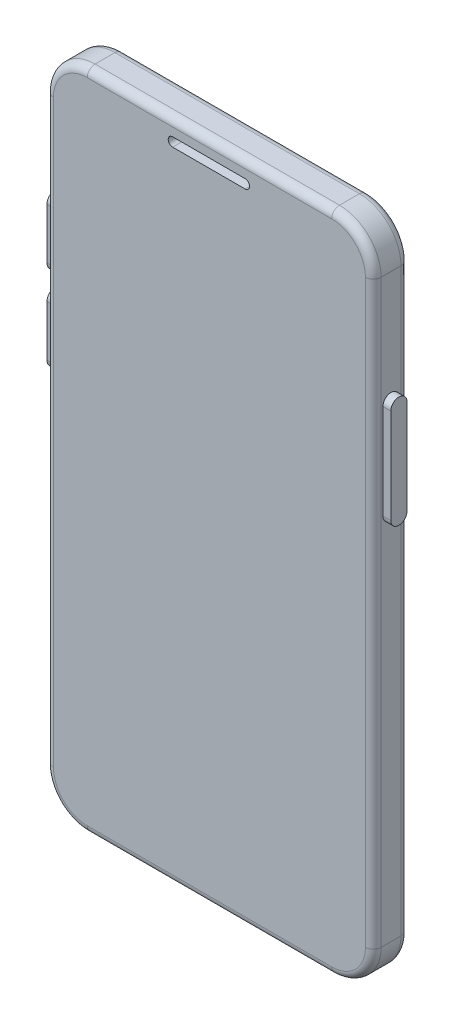
SolidWorks part; units mm, degrees
ref_plane "Front Plane" through (0, 0, 0) normal (0, 0, 1) x (1, 0, 0)
ref_plane "Top Plane" through (0, 0, 0) normal (0, 1, 0) x (1, 0, 0)
ref_plane "Right Plane" through (0, 0, 0) normal (1, 0, 0) x (0, 0, -1)
sketch "Sketch1" plane through (0, 0, 0) normal (0, 0, 1) x (1, 0, 0)
  line L1 (0, 0) -> (70.9, 0)
  line L2 (0, 0) -> (0, -143.6)
  line L3 (0, -143.6) -> (70.9, -143.6)
  line L4 (70.9, 0) -> (70.9, -143.6)
  dimension "D1" = 70.9
  dimension "D2" = 143.6
extrude "Boss-Extrude1" add sketch "Sketch1" along normal blind 7.7
fillet "Fillet1" radius 9 4 edges at (0, -143.6, 3.85) (70.9, -143.6, 3.85) (0, 0, 3.85) (70.9, 0, 3.85)
sketch "Sketch2" plane through (70.9, -8.3279, 0) normal (1, 0, 0) x (0, 0, -1)
  line L0 (-3.85, -9) -> (-3.85, -134.6) construction
  line L5 (-5.6051, -45.632) -> (-5.6051, -25.0925)
  line L7 (-2.0949, -45.632) -> (-2.0949, -25.0925)
  line L8 (-5.6051, -45.632) -> (-2.0949, -25.0925) construction
  line L9 (-5.6051, -25.0925) -> (-2.0949, -45.632) construction
  arc A0 (-2.0949, -25.0925) -> (-5.6051, -25.0925) centre (-3.85, -25.0925) ccw
  arc A1 (-2.0949, -45.632) -> (-5.6051, -45.632) centre (-3.85, -45.632) cw
  point P6 (-3.85, -35.3623)
extrude "Boss-Extrude2" add sketch "Sketch2" along normal blind 1.7 contours L5 A0 L7 A1
sketch "Sketch3" plane through (0, 0, 0) normal (-1, 0, 0) x (0, 0, 1)
  line L0 (3.85, -9) -> (3.85, -120.3552) construction
  line L1 (7.7, -9) -> (0, -9) construction
  line L2 (0, -46.37) -> (7.7, -46.37)
  line L4 (1.9886, -42.7498) -> (1.9886, -31.7534)
  line L6 (5.7114, -42.7498) -> (5.7114, -31.7534)
  line L7 (1.9886, -42.7498) -> (5.7114, -31.7534) construction
  line L8 (1.9886, -31.7534) -> (5.7114, -42.7498) construction
  line L9 (0, -9) -> (0, -134.6) construction
  line L10 (7.7, -9) -> (7.7, -134.6) construction
  line L11 (1.9886, -49.9901) -> (1.9886, -60.9865)
  line L12 (5.7114, -49.9901) -> (5.7114, -60.9865)
  arc A0 (5.7114, -31.7534) -> (1.9886, -31.7534) centre (3.85, -31.7534) ccw
  arc A1 (5.7114, -42.7498) -> (1.9886, -42.7498) centre (3.85, -42.7498) cw
  arc A2 (5.7114, -49.9901) -> (1.9886, -49.9901) centre (3.85, -49.9901) ccw
  arc A3 (5.7114, -60.9865) -> (1.9886, -60.9865) centre (3.85, -60.9865) cw
  point P4 (3.85, -37.2516)
extrude "Boss-Extrude3" add sketch "Sketch3" along normal blind 1.7 contours A3 L12 A2 L11 | A0 L6 A1 L4
sketch "Sketch4" plane through (0, 0, 0) normal (-1, 0, 0) x (0, 0, 1)
  line L0 (3.85, -9) -> (3.85, -29.8921) construction
  line L5 (7.7, -9) -> (0, -9) construction
  line L7 (2.1833, -25.5824) -> (5.5167, -25.5824)
  line L8 (2.1833, -25.5824) -> (2.1833, -19.446)
  line L9 (2.1833, -19.446) -> (5.5167, -19.446)
  line L10 (5.5167, -25.5824) -> (5.5167, -19.446)
  line L11 (2.1833, -25.5824) -> (5.5167, -19.446) construction
  line L12 (2.1833, -19.446) -> (5.5167, -25.5824) construction
  arc A0 (5.7114, -31.7534) -> (1.9886, -31.7534) centre (3.85, -31.7534) ccw construction
  point P7 (3.85, -22.5142)
extrude "Cut-Extrude1" cut sketch "Sketch4" against normal blind 1.7
sketch "Sketch5" plane through (1.7, 0, 0) normal (-1, 0, 0) x (0, 0, 1)
  line L0 (2.1833, -25.5824) -> (5.5167, -25.5824) construction
  line L1 (3.7868, -19.6552) -> (2.4039, -19.6552)
  line L2 (3.7868, -19.6552) -> (3.7868, -25.5824)
  line L3 (3.7868, -25.5824) -> (2.4039, -25.5824)
  line L4 (2.4039, -19.6552) -> (2.4039, -25.5824)
extrude "Boss-Extrude4" add sketch "Sketch5" along normal blind 1.7
sketch "Sketch6" plane through (0, 0, 0) normal (0, 0, -1) x (-1, 0, 0)
  line L3 (-58.2914, -28.4592) -> (-58.2914, -9.3124)
  line L5 (-66.1104, -28.4592) -> (-66.1104, -9.3124)
  arc A1 (-58.2914, -9.3124) -> (-66.1104, -9.3124) centre (-62.2009, -9.3124) ccw
  arc A2 (-58.2914, -28.4592) -> (-66.1104, -28.4592) centre (-62.2009, -28.4592) cw
  point P5 (-62.2009, -18.8858)
extrude "Boss-Extrude5" add sketch "Sketch6" along normal blind 1.7 contours A2 L3 A1 L5
sketch "Sketch7" plane through (0, 0, -1.7) normal (0, 0, -1) x (-1, 0, 0)
  line L0 (-62.2009, -32.3687) -> (-62.2009, -5.4029) construction
  arc A0 (-66.1104, -28.4592) -> (-58.2914, -28.4592) centre (-62.2009, -28.4592) ccw construction
  arc A1 (-58.2914, -9.3124) -> (-66.1104, -9.3124) centre (-62.2009, -9.3124) ccw construction
  circle A2 centre (-62.2009, -18.8858) radius 1.7666
extrude "Cut-Extrude2" cut sketch "Sketch7" against normal blind 0.7
sketch "Sketch8" plane through (0, -143.6, 0) normal (0, -1, 0) x (-1, 0, 0)
  line L0 (-9, -3.85) -> (-61.9, -3.85) construction
  line L1 (-9, -7.7) -> (-9, 0) construction
  line L2 (-61.9, 0) -> (-61.9, -7.7) construction
  line L4 (-32.3826, -2.5962) -> (-38.5174, -2.5962)
  line L6 (-32.3826, -5.1038) -> (-38.5174, -5.1038)
  line L8 (-32.3826, -2.5962) -> (-38.5174, -5.1038) construction
  line L9 (-32.3826, -5.1038) -> (-38.5174, -2.5962) construction
  arc A0 (-38.5174, -2.5962) -> (-38.5174, -5.1038) centre (-38.5174, -3.85) ccw
  arc A1 (-32.3826, -5.1038) -> (-32.3826, -2.5962) centre (-32.3826, -3.85) ccw
  point P6 (-35.45, -3.85)
extrude "Cut-Extrude3" cut sketch "Sketch8" against normal blind 6.7 contours L6 A1 L4 A0
sketch "Sketch9" plane through (0, -143.6, 0) normal (0, -1, 0) x (1, 0, 0)
  line L0 (9, 3.85) -> (61.9, 3.85) construction
  line L1 (9, 7.7) -> (9, 0) construction
  line L2 (61.9, 0) -> (61.9, 7.7) construction
  circle A0 centre (44.6241, 3.85) radius 1.2348
extrude "Cut-Extrude4" cut sketch "Sketch9" against normal blind 4.7
pattern_linear "LPattern1" count 5 spacing 4 along (1, 0, 0) of "Cut-Extrude4"
sketch "Sketch10" plane through (0, -143.6, 0) normal (0, -1, 0) x (1, 0, 0)
  line L0 (9, 3.85) -> (61.8588, 3.85) construction
  line L1 (9, 7.7) -> (9, 0) construction
  circle A0 centre (60.6241, 3.85) radius 1.2348 construction
  circle A1 centre (26.0345, 3.85) radius 1.4033
  point P9 (26.6228, 3.85)
  point P10 (26.0345, 3.85)
extrude "Cut-Extrude5" cut sketch "Sketch10" against normal blind 4.7
pattern_linear "LPattern2" count 5 spacing 4 along (-1, 0, 0) of "Cut-Extrude5"
sketch "Sketch11" plane through (0, -1.7385, 7.7) normal (0, 0, 1) x (1, 0, 0)
  line L0 (2.3868, -2.8954) -> (68.264, -2.636) construction
  line L2 (27.4924, -3.7341) -> (43.1584, -3.7341)
  line L4 (27.4924, -1.7974) -> (43.1584, -1.7974)
  line L6 (27.4924, -3.7341) -> (43.1584, -1.7974) construction
  line L7 (27.4924, -1.7974) -> (43.1584, -3.7341) construction
  arc A2 (43.1584, -3.7341) -> (43.1584, -1.7974) centre (43.1584, -2.7657) ccw
  arc A3 (27.4924, -3.7341) -> (27.4924, -1.7974) centre (27.4924, -2.7657) cw
  point P8 (35.3254, -2.7657)
extrude "Cut-Extrude6" cut sketch "Sketch11" against normal blind 2.7
fillet "Fillet2" radius 1.7 8 edges at (68.264, -2.636, 7.7) (70.9, -71.8, 7.7) (68.264, -140.964, 7.7) (35.45, -143.6, 7.7) (2.636, -140.964, 7.7) (0, -71.8, 7.7) (2.636, -2.636, 7.7) (35.45, 0, 7.7)
fillet "Fillet3" radius 1.7 8 edges at (68.264, -140.964, 0) (35.45, -143.6, 0) (2.636, -140.964, 0) (0, -71.8, 0) (2.636, -2.636, 0) (35.45, 0, 0) (68.264, -2.636, 0) (70.9, -71.8, 0)
